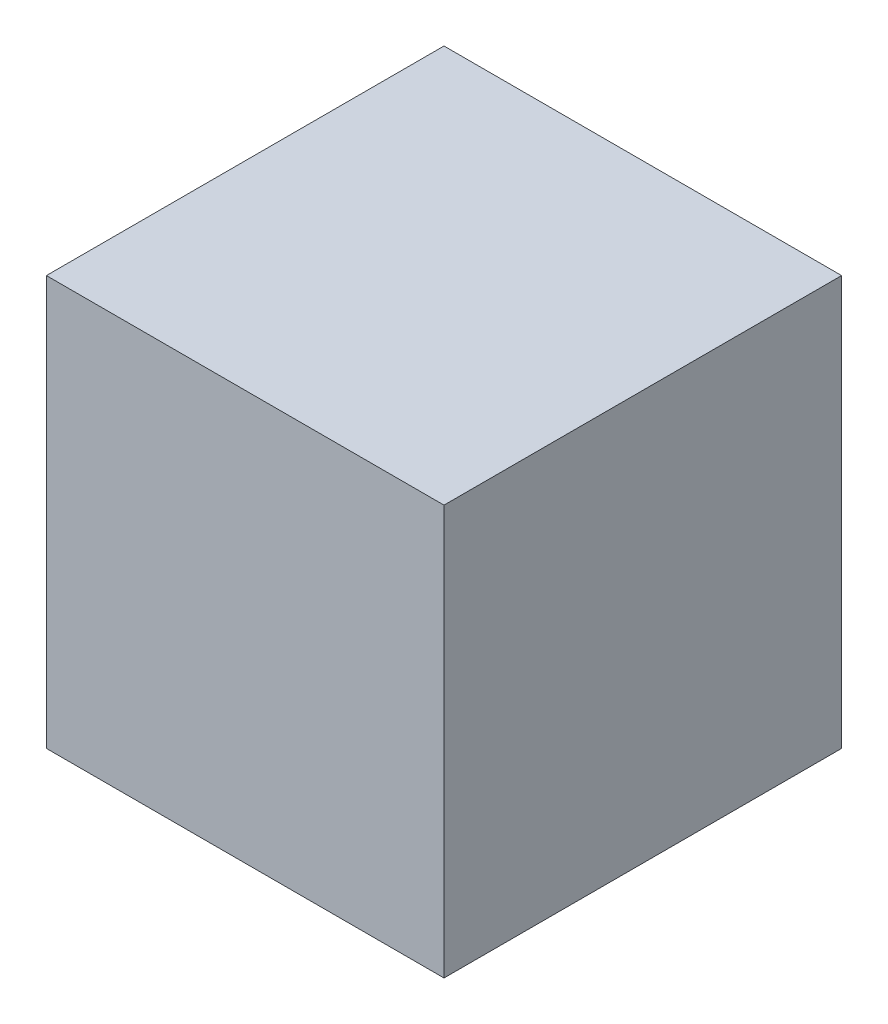
SolidWorks part; units mm, degrees
ref_plane "前视基准面" through (0, 0, 0) normal (0, 0, 1) x (1, 0, 0)
ref_plane "上视基准面" through (0, 0, 0) normal (0, 1, 0) x (1, 0, 0)
ref_plane "右视基准面" through (0, 0, 0) normal (1, 0, 0) x (0, 0, -1)
other "Configuration Table"
sketch "草图1" plane through (0, 0, 0) normal (0, 1, 0) x (1, 0, 0)
  line L1 (-50, 50) -> (50, 50)
  line L2 (-50, 50) -> (-50, -50)
  line L3 (-50, -50) -> (50, -50)
  line L4 (50, 50) -> (50, -50)
  line L5 (-50, 50) -> (50, -50) construction
  line L6 (-50, -50) -> (50, 50) construction
  point P0 (0, 0)
  dimension "D1" = 100
  dimension "D2" = 100
extrude "凸台-拉伸1" add sketch "草图1" along normal blind 3
sketch "草图2" plane through (0, 0, 0) normal (0, -1, 0) x (1, 0, 0)
  line L0 (47, -47) -> (47, 47)
  line L1 (47, 47) -> (-47, 47)
  line L2 (-47, 47) -> (-47, -47)
  line L3 (-47, -47) -> (47, -47)
  line L4 (50, -50) -> (50, 50)
  line L5 (50, 50) -> (-50, 50)
  line L6 (-50, 50) -> (-50, -50)
  line L7 (-50, -50) -> (50, -50)
  line L8 (50, -50) -> (50, 50)
  line L9 (50, 50) -> (-50, 50)
  line L10 (-50, 50) -> (-50, -50)
  line L11 (-50, -50) -> (50, -50)
  dimension "D1" = 0
  dimension "D2" = 3
extrude "凸台-拉伸2" add sketch "草图2" along normal blind 100
